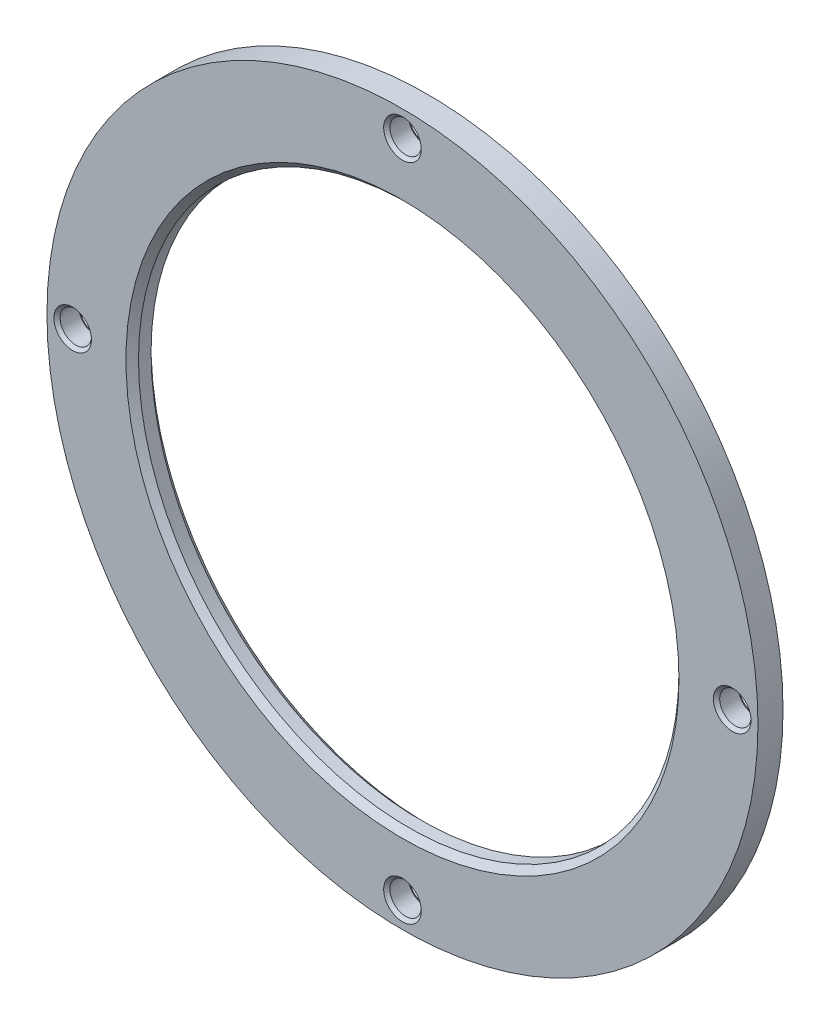
SolidWorks part; units mm, degrees
ref_plane "Front Plane" through (0, 0, 0) normal (1, 0, 0) x (0, 1, 0)
ref_plane "Top Plane" through (0, 0, 0) normal (0, 0, 1) x (0, 1, 0)
ref_plane "Right Plane" through (0, 0, 0) normal (0, 1, 0) x (-1, 0, 0)
sketch "Sketch1" plane through (0, 0, 0) normal (0, 0, 1) x (0, 1, 0)
  circle A0 centre (0, 0) radius 28.35
  dimension "D1" = 56.7
extrude "Extrude-Thin1" add sketch "Sketch1" along normal blind 2 thin thin type one direction reverse wall 6.8
chamfer "Chamfer1" distance 0.5 angle 45 2 edges at (0, 21.55, 2) (0, 21.55, 0)
sketch "Sketch2" plane through (0, 0, 0) normal (0, 0, 1) x (0, 1, 0)
  circle A0 centre (0, 26.3) radius 1.25
  circle A2 centre (0, 0) radius 22.05 construction
  point P2 (0, 0)
  dimension "D1" = 26.3
  dimension "D2" = 2.5
extrude "Cut-Extrude1" cut sketch "Sketch2" along normal through all
pattern_circular "CirPattern1" count 4 over 360 about axis through (0, 0, 0) along (0, 0, 1) of "Cut-Extrude1"
chamfer "Chamfer2" distance 0.25 angle 45 8 edges at (-25.05, 0, 0) (0, 25.05, 0) (25.05, 0, 0) (0, -25.05, 0) (0, -25.05, 2) (25.05, 0, 2) (0, 25.05, 2) (-25.05, 0, 2)
